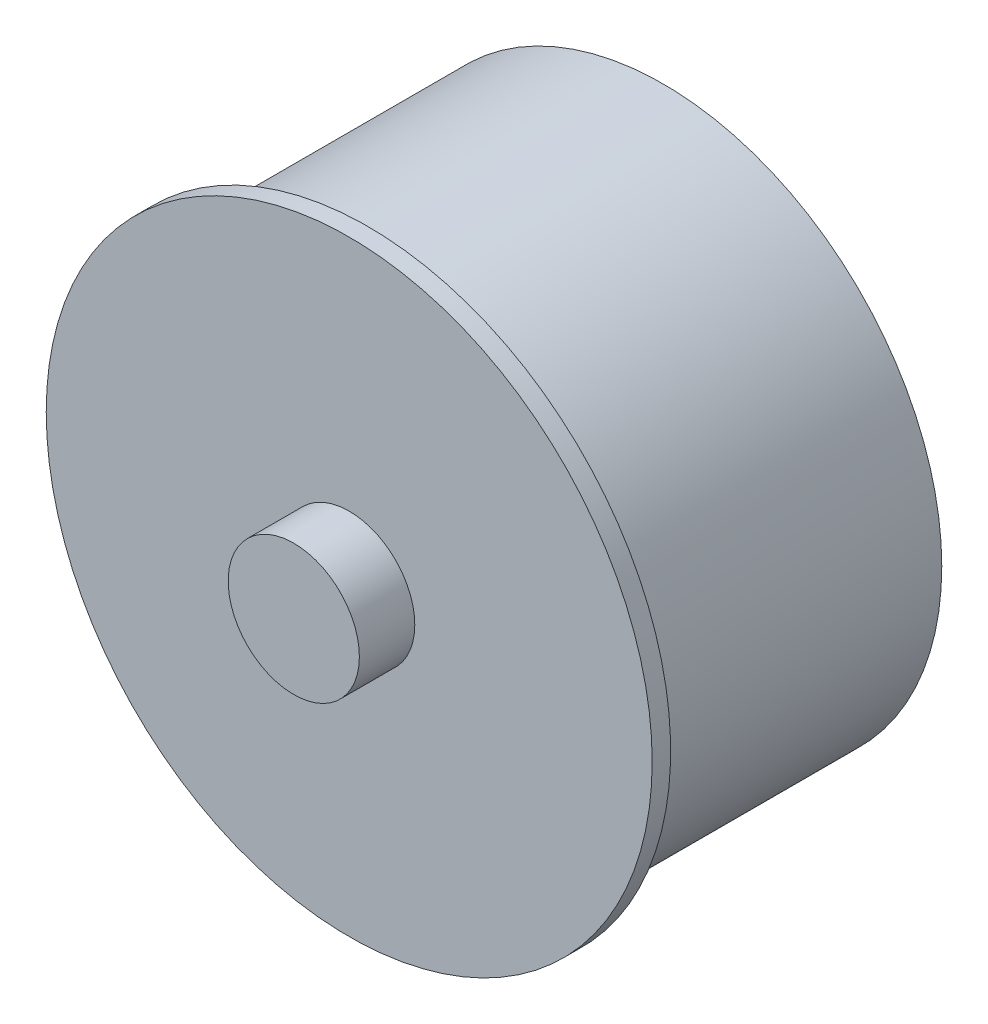
SolidWorks part; units mm, degrees
ref_plane "前视基准面" through (0, 0, 0) normal (0, 0, 1) x (1, 0, 0)
ref_plane "上视基准面" through (0, 0, 0) normal (0, 1, 0) x (1, 0, 0)
ref_plane "右视基准面" through (0, 0, 0) normal (1, 0, 0) x (0, 0, -1)
other "Configuration Table"
sketch "草图1" plane through (0, 0, 0) normal (0, 0, 1) x (1, 0, 0)
  circle A0 centre (0, 0) radius 16.4
  dimension "D1" = 32.8
extrude "凸台-拉伸1" add sketch "草图1" along normal blind 17
sketch "草图2" plane through (0, 0, 17) normal (0, 0, 1) x (1, 0, 0)
  circle A0 centre (0, 0) radius 3.55
  dimension "D1" = 7.1
extrude "凸台-拉伸2" add sketch "草图2" along normal blind 3
sketch "草图3" plane through (0, 0, 0) normal (0, 0, -1) x (-1, 0, 0)
  circle A0 centre (0, 0) radius 10.075
  dimension "D1" = 20.15
extrude "凸台-拉伸3" add sketch "草图3" along normal blind 2 separate body
sketch "草图7" plane through (0, 0, -2) normal (0, 0, -1) x (-1, 0, 0)
  line L0 (0, 0) -> (0, 8) construction
  line L1 (0, 0) -> (8, 0) construction
  line L2 (0, 0) -> (0, -8) construction
  line L3 (0, 0) -> (-8, 0) construction
  circle A0 centre (0, 8) radius 1.05
  circle A1 centre (8, 0) radius 1.05
  circle A2 centre (0, -8) radius 1.05
  circle A3 centre (-8, 0) radius 1.05
  point P13 (0, 0)
  dimension "D1" = 4
extrude "切除-拉伸3" cut sketch "草图7" against normal blind 10 contours A0 | A1 | A2 | A3
sketch "Sketch3" plane through (0, 0, 0) normal (0, 0, -1) x (-1, 0, 0)
  circle A0 centre (0, 0) radius 15.075
  circle A1 centre (0, 0) radius 16.4
extrude "Cut-Extrude1" cut sketch "Sketch3" against normal blind 16
